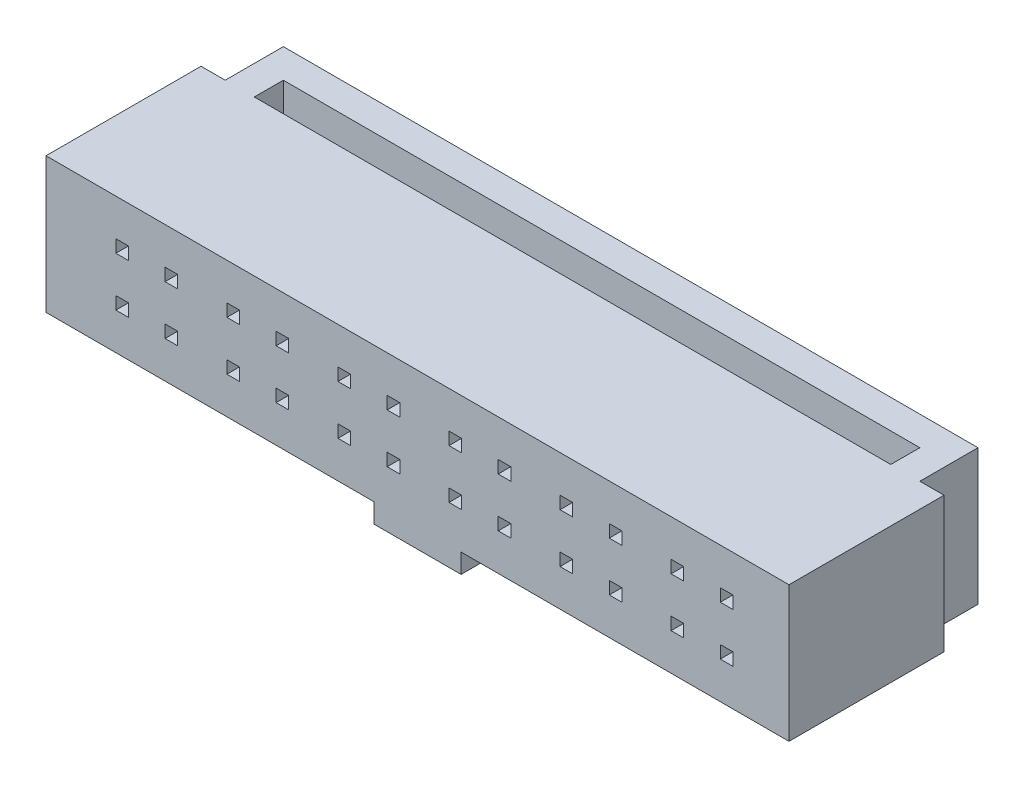
SolidWorks part; units mm, degrees
ref_plane "Front Plane" through (0, 0, 0) normal (0, 0, 1) x (1, 0, 0)
ref_plane "Top Plane" through (0, 0, 0) normal (0, 1, 0) x (1, 0, 0)
ref_plane "Right Plane" through (0, 0, 0) normal (1, 0, 0) x (0, 0, -1)
sketch "Sketch1" plane through (0, 0, 0) normal (0, 0, 1) x (1, 0, 0)
  line L0 (2.1824, 30.9126) -> (19.1024, 30.9126)
  line L1 (5.7874, 32.8176) -> (6.4374, 32.8176)
  line L2 (6.4374, 32.8176) -> (6.4374, 33.4676)
  line L3 (8.3274, 32.8176) -> (8.9774, 32.8176)
  line L4 (8.9774, 32.8176) -> (8.9774, 33.4676)
  line L5 (19.1024, 30.9126) -> (19.1024, 29.9126)
  line L6 (19.1024, 29.9126) -> (23.6024, 29.9126)
  line L7 (23.6024, 29.9126) -> (23.6024, 30.9126)
  line L8 (23.6024, 30.9126) -> (40.5224, 30.9126)
  line L9 (40.5224, 30.9126) -> (40.5224, 37.9126)
  line L10 (40.5224, 37.9126) -> (2.1824, 37.9126)
  line L11 (2.1824, 37.9126) -> (2.1824, 30.9126)
  line L12 (6.4374, 35.3576) -> (6.4374, 36.0076)
  line L13 (5.7874, 35.3576) -> (6.4374, 35.3576)
  line L14 (8.9774, 35.3576) -> (8.9774, 36.0076)
  line L15 (8.3274, 35.3576) -> (8.9774, 35.3576)
  line L16 (8.9774, 36.0076) -> (8.3274, 36.0076)
  line L17 (8.3274, 36.0076) -> (8.3274, 35.3576)
  line L18 (6.4374, 36.0076) -> (5.7874, 36.0076)
  line L19 (5.7874, 36.0076) -> (5.7874, 35.3576)
  line L20 (6.4374, 33.4676) -> (5.7874, 33.4676)
  line L21 (5.7874, 33.4676) -> (5.7874, 32.8176)
  line L22 (8.9774, 33.4676) -> (8.3274, 33.4676)
  line L23 (8.3274, 33.4676) -> (8.3274, 32.8176)
  line L24 (8.9774, 35.3576) -> (11.5174, 35.3576) construction
  line L25 (14.7074, 32.8176) -> (14.7074, 33.4676)
  line L26 (12.1674, 35.3576) -> (12.1674, 36.0076)
  line L27 (11.5174, 33.4676) -> (11.5174, 32.8176)
  line L28 (11.5174, 32.8176) -> (12.1674, 32.8176)
  line L29 (12.1674, 32.8176) -> (12.1674, 33.4676)
  line L30 (11.5174, 36.0076) -> (11.5174, 35.3576)
  line L31 (12.1674, 33.4676) -> (11.5174, 33.4676)
  line L32 (14.7074, 35.3576) -> (14.7074, 36.0076)
  line L33 (14.7074, 33.4676) -> (14.0574, 33.4676)
  line L34 (14.0574, 33.4676) -> (14.0574, 32.8176)
  line L35 (14.7074, 35.3576) -> (17.2474, 35.3576) construction
  line L36 (12.1674, 36.0076) -> (11.5174, 36.0076)
  line L37 (14.0574, 36.0076) -> (14.0574, 35.3576)
  line L38 (14.0574, 32.8176) -> (14.7074, 32.8176)
  line L39 (14.0574, 35.3576) -> (14.7074, 35.3576)
  line L40 (14.7074, 36.0076) -> (14.0574, 36.0076)
  line L41 (11.5174, 35.3576) -> (12.1674, 35.3576)
  line L42 (20.4374, 32.8176) -> (20.4374, 33.4676)
  line L43 (17.8974, 35.3576) -> (17.8974, 36.0076)
  line L44 (17.2474, 33.4676) -> (17.2474, 32.8176)
  line L45 (17.2474, 32.8176) -> (17.8974, 32.8176)
  line L46 (17.8974, 32.8176) -> (17.8974, 33.4676)
  line L47 (17.2474, 36.0076) -> (17.2474, 35.3576)
  line L48 (17.8974, 33.4676) -> (17.2474, 33.4676)
  line L49 (20.4374, 35.3576) -> (20.4374, 36.0076)
  line L50 (20.4374, 33.4676) -> (19.7874, 33.4676)
  line L51 (19.7874, 33.4676) -> (19.7874, 32.8176)
  line L52 (20.4374, 35.3576) -> (22.9774, 35.3576) construction
  line L53 (17.8974, 36.0076) -> (17.2474, 36.0076)
  line L54 (19.7874, 36.0076) -> (19.7874, 35.3576)
  line L55 (19.7874, 32.8176) -> (20.4374, 32.8176)
  line L56 (19.7874, 35.3576) -> (20.4374, 35.3576)
  line L57 (20.4374, 36.0076) -> (19.7874, 36.0076)
  line L58 (17.2474, 35.3576) -> (17.8974, 35.3576)
  line L59 (26.1674, 32.8176) -> (26.1674, 33.4676)
  line L60 (23.6274, 35.3576) -> (23.6274, 36.0076)
  line L61 (22.9774, 33.4676) -> (22.9774, 32.8176)
  line L62 (22.9774, 32.8176) -> (23.6274, 32.8176)
  line L63 (23.6274, 32.8176) -> (23.6274, 33.4676)
  line L64 (22.9774, 36.0076) -> (22.9774, 35.3576)
  line L65 (23.6274, 33.4676) -> (22.9774, 33.4676)
  line L66 (26.1674, 35.3576) -> (26.1674, 36.0076)
  line L67 (26.1674, 33.4676) -> (25.5174, 33.4676)
  line L68 (25.5174, 33.4676) -> (25.5174, 32.8176)
  line L69 (26.1674, 35.3576) -> (28.7074, 35.3576) construction
  line L70 (23.6274, 36.0076) -> (22.9774, 36.0076)
  line L71 (25.5174, 36.0076) -> (25.5174, 35.3576)
  line L72 (25.5174, 32.8176) -> (26.1674, 32.8176)
  line L73 (25.5174, 35.3576) -> (26.1674, 35.3576)
  line L74 (26.1674, 36.0076) -> (25.5174, 36.0076)
  line L75 (22.9774, 35.3576) -> (23.6274, 35.3576)
  line L76 (31.8974, 32.8176) -> (31.8974, 33.4676)
  line L77 (29.3574, 35.3576) -> (29.3574, 36.0076)
  line L78 (28.7074, 33.4676) -> (28.7074, 32.8176)
  line L79 (28.7074, 32.8176) -> (29.3574, 32.8176)
  line L80 (29.3574, 32.8176) -> (29.3574, 33.4676)
  line L81 (28.7074, 36.0076) -> (28.7074, 35.3576)
  line L82 (29.3574, 33.4676) -> (28.7074, 33.4676)
  line L83 (31.8974, 35.3576) -> (31.8974, 36.0076)
  line L84 (31.8974, 33.4676) -> (31.2474, 33.4676)
  line L85 (31.2474, 33.4676) -> (31.2474, 32.8176)
  line L86 (31.8974, 35.3576) -> (34.4374, 35.3576) construction
  line L87 (29.3574, 36.0076) -> (28.7074, 36.0076)
  line L88 (31.2474, 36.0076) -> (31.2474, 35.3576)
  line L89 (31.2474, 32.8176) -> (31.8974, 32.8176)
  line L90 (31.2474, 35.3576) -> (31.8974, 35.3576)
  line L91 (31.8974, 36.0076) -> (31.2474, 36.0076)
  line L92 (28.7074, 35.3576) -> (29.3574, 35.3576)
  line L93 (37.6274, 32.8176) -> (37.6274, 33.4676)
  line L94 (35.0874, 35.3576) -> (35.0874, 36.0076)
  line L95 (34.4374, 33.4676) -> (34.4374, 32.8176)
  line L96 (34.4374, 32.8176) -> (35.0874, 32.8176)
  line L97 (35.0874, 32.8176) -> (35.0874, 33.4676)
  line L98 (34.4374, 36.0076) -> (34.4374, 35.3576)
  line L99 (35.0874, 33.4676) -> (34.4374, 33.4676)
  line L100 (37.6274, 35.3576) -> (37.6274, 36.0076)
  line L101 (37.6274, 33.4676) -> (36.9774, 33.4676)
  line L102 (36.9774, 33.4676) -> (36.9774, 32.8176)
  line L104 (35.0874, 36.0076) -> (34.4374, 36.0076)
  line L105 (36.9774, 36.0076) -> (36.9774, 35.3576)
  line L106 (36.9774, 32.8176) -> (37.6274, 32.8176)
  line L107 (36.9774, 35.3576) -> (37.6274, 35.3576)
  line L108 (37.6274, 36.0076) -> (36.9774, 36.0076)
  line L109 (34.4374, 35.3576) -> (35.0874, 35.3576)
  dimension "D1" = 2.54
  dimension "D2" = 2.54
  dimension "D3" = 2.54
  dimension "D4" = 2.54
  dimension "D5" = 2.54
extrude "Boss-Extrude1" add sketch "Sketch1" along normal blind 8
sketch "Sketch2" plane through (0, 37.9126, 0) normal (0, 1, 0) x (1, 0, 0)
  line L0 (3.4297, 0) -> (3.4297, 3)
  line L1 (40.5224, 0) -> (2.1824, 0) construction
  line L2 (3.4297, 3) -> (39.275, 3)
  line L3 (21.3524, 0) -> (21.3524, 5.3092) construction
  line L4 (39.275, 0) -> (39.275, 3)
  line L5 (4.9297, 0) -> (4.9297, 1.5)
  line L6 (4.9297, 1.5) -> (37.775, 1.5)
  line L7 (37.775, 0) -> (37.775, 1.5)
  line L8 (39.275, 0) -> (37.775, 0)
  line L9 (4.9297, 0) -> (3.4297, 0)
  point P13 (21.3524, 1.5)
  point P14 (21.3524, 3)
  dimension "D1" = 3
  dimension "D3" = 1.5
extrude "Boss-Extrude2" add sketch "Sketch2" against normal up to surface (7 mm away) up to face at (32.0624, 30.9126, 4)
